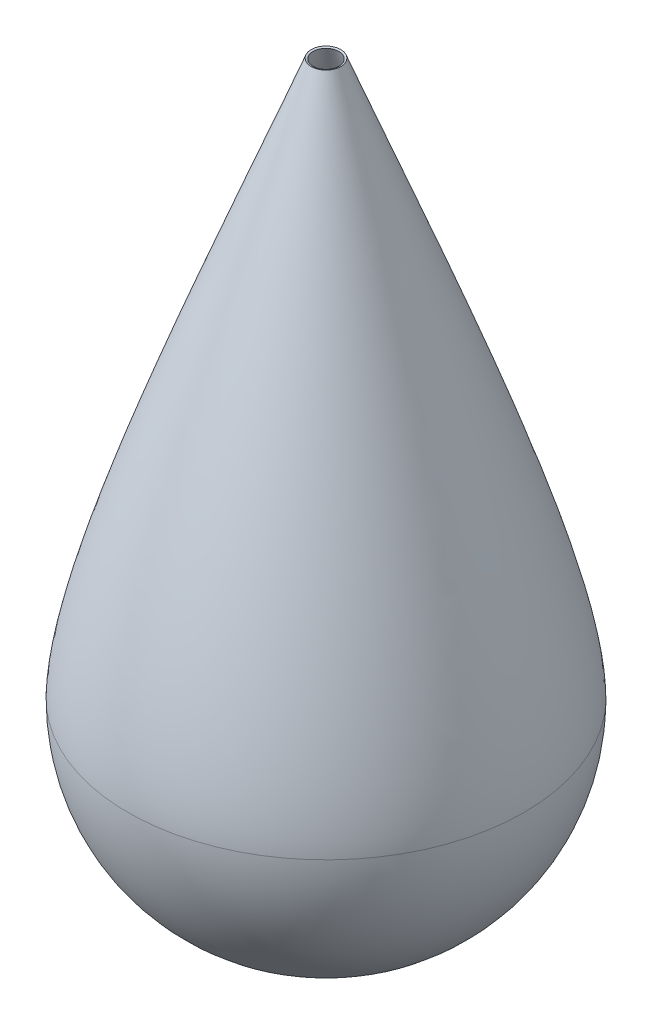
SolidWorks part; units mm, degrees
ref_plane "Front Plane" through (0, 0, 0) normal (0, 0, 1) x (1, 0, 0)
ref_plane "Top Plane" through (0, 0, 0) normal (0, 1, 0) x (1, 0, 0)
ref_plane "Right Plane" through (0, 0, 0) normal (1, 0, 0) x (0, 0, -1)
sketch "Sketch1" plane through (0, 0, 0) normal (0, 0, 1) x (1, 0, 0)
  line L0 (0, 0) -> (0, 46.6016) construction
  line L12 (-17.0428, 280) -> (7.4572, 280) construction
  line L14 (7.4572, 280) -> (6.5228, 279.6436)
  line L15 (0, -99) -> (0, -100)
  circle A4 centre (0, 0) radius 100 construction
  arc A5 (100, 0) -> (0, -100) centre (0, 0) cw
  arc A6 (99, -0.0113) -> (0, -99) centre (0, 0) cw
  arc A7 (100, 0) -> (-0.1286, -99.9999) centre (0, 0) cw construction
  arc A8 (99, -0.0113) -> (-0.1273, -98.9999) centre (0, 0) cw construction
  spline S0 degree 3 poles (100, 0) (98.8521, 50.8388) (43.3962, 185.7923) (7.4572, 280) knots 0 0 0 0 1 1 1 1
  spline S1 degree 1 poles (99, -0.0113) (6.5228, 279.6436) knots 0 0 1 1 construction
  spline S2 degree 3 poles (99, -0.0113) (98.991, 0.3859) (98.9668, 1.1725) (98.892, 2.807) (98.7504, 4.9207) (98.5046, 7.5804) (98.078, 11.2819) (97.3632, 16.194) (96.2278, 22.519) (94.828, 29.2503) (92.6273, 38.7352) (89.2827, 51.4879) (84.4278, 68.0386) (78.8397, 85.6516) (72.6268, 104.1425) (63.6541, 129.7222) (53.8647, 156.3229) (43.6914, 183.2117) (35.9777, 203.3392) (28.2882, 223.2448) (21.9907, 239.4957) (17.0731, 252.2022) (13.4579, 261.5637) (10.5197, 269.2001) (8.2155, 275.2116) (7.0883, 278.1612) (6.5228, 279.6436) knots 0.000075 0.000075 0.000075 0.000075 0.007887 0.015699 0.031323 0.046946 0.06257 0.093818 0.125066 0.156313 0.187561 0.250056 0.312552 0.375047 0.437542 0.500037 0.625028 0.687523 0.750019 0.812514 0.875009 0.906257 0.937505 0.968752 0.984376 1 1 1 1
  point P13 (-4.7928, 280)
  dimension "D1" = 200
  dimension "D2" = 280
  dimension "D3" = 1
  dimension "D4" = 24.5
revolve "Revolve4" add sketch "Sketch1" angle 360 about L0
